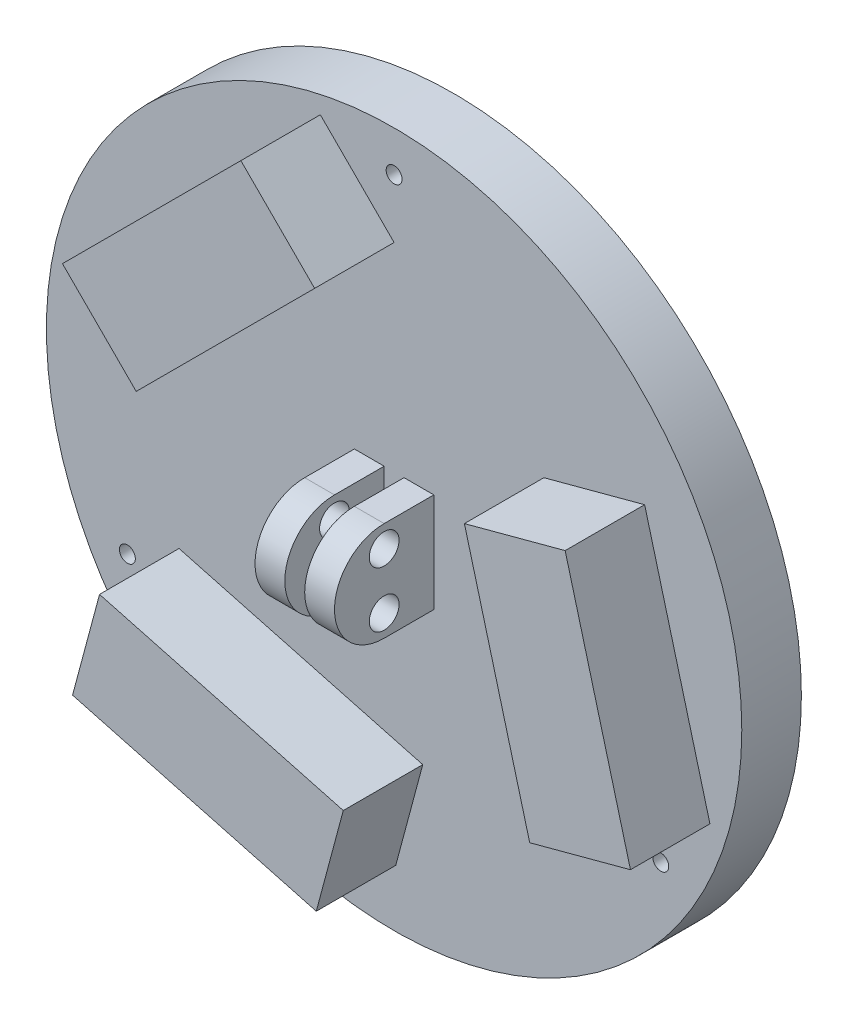
SolidWorks part; units mm, degrees
ref_plane "Front Plane" through (0, 0, 0) normal (0, 0, 1) x (1, 0, 0)
ref_plane "Top Plane" through (0, 0, 0) normal (0, 1, 0) x (1, 0, 0)
ref_plane "Right Plane" through (0, 0, 0) normal (1, 0, 0) x (0, 0, -1)
sketch "Sketch2" plane through (0, 0, 0) normal (0, 0, 1) x (1, 0, 0)
  circle A0 centre (0, 0) radius 35
  point P11 (0, 0)
  dimension "D1" = 70
extrude "Boss-Extrude1" add sketch "Sketch2" along normal blind 6 contours A0
sketch "Sketch3" plane through (0, 0, 6) normal (0, 0, 1) x (1, 0, 0)
  circle A0 centre (0, 30.9143) radius 0.8
  circle A1 centre (26.8468, -15.5857) radius 0.8
  circle A2 centre (-26.8468, -15.5857) radius 0.8
  point P8 (0, -0.0857)
  dimension "D1" = 1.6
  dimension "D3" = 31
  dimension "D2" = 3
extrude "Cut-Extrude1" cut sketch "Sketch3" against normal blind 6
sketch "Sketch4" plane through (0, 0, 6) normal (0, 0, 1) x (1, 0, 0)
  circle A0 centre (0, 0) radius 0.6
  dimension "D1" = 1.2
extrude "Cut-Extrude2" cut sketch "Sketch4" against normal blind 6
sketch "Sketch5" plane through (0, 0, 6) normal (0, 0, 1) x (1, 0, 0)
  line L1 (1, 5) -> (4, 5)
  line L2 (1, 5) -> (1, -5)
  line L3 (1, -5) -> (4, -5)
  line L4 (4, 5) -> (4, -5)
  line L5 (-1, 5) -> (-4, 5)
  line L6 (-1, 5) -> (-1, -5)
  line L7 (-1, -5) -> (-4, -5)
  line L8 (-4, 5) -> (-4, -5)
  dimension "D1" = 10
  dimension "D2" = 3
  dimension "D3" = 4
  dimension "D4" = 5
  dimension "D5" = 4
  dimension "D6" = 5
extrude "Boss-Extrude2" add sketch "Sketch5" along normal blind 10
sketch "Sketch6" plane through (4, 0, 0) normal (1, 0, 0) x (0, 0, -1)
  line L1 (-16, 5) -> (-6, 5) construction
  line L2 (-11, 5) -> (-16, 5)
  line L3 (-16, 5) -> (-16, -5)
  line L5 (-16, -5) -> (-11, -5)
  line L6 (-16, 5) -> (-11, 5)
  arc A2 (-11, -5) -> (-11, 5) centre (-11, 0) cw
  line M5 (-6, 5) -> (-16, 5)
  line M6 (-16, 5) -> (-16, -5)
  line M7 (-16, -5) -> (-6, -5)
extrude "Cut-Extrude3" cut sketch "Sketch6" against normal through all contours A2 M6 M5 | A2 L3 M7
sketch "Sketch7" plane through (4, 0, 0) normal (1, 0, 0) x (0, 0, -1)
  line L1 (-11, 5) -> (-6, 5) construction
  line L2 (-11, -5) -> (-6, -5) construction
  circle A2 centre (-11, 2.8) radius 1.5
  circle A3 centre (-11, -2.8) radius 1.5
  dimension "D1" = 2.2
  dimension "D2" = 2.2
  dimension "D4" = 3
extrude "Cut-Extrude4" cut sketch "Sketch7" against normal through all
sketch "Sketch8" plane through (0, 0, 6) normal (0, 0, 1) x (1, 0, 0)
  line L0 (-7.4246, 32.4246) -> (0, 25)
  line L1 (-7.4246, 32.4246) -> (-25.3851, 14.4641)
  line L2 (0, 25) -> (-17.9605, 7.0395)
  line L3 (-25.3851, 14.4641) -> (-17.9605, 7.0395)
  line L4 (31.7929, -9.7824) -> (21.6506, -12.5)
  line L5 (31.7929, -9.7824) -> (25.2189, 14.7521)
  line L6 (25.2189, 14.7521) -> (15.0766, 12.0345)
  line L7 (21.6506, -12.5) -> (15.0766, 12.0345)
  line L8 (-24.3682, -22.6422) -> (-21.6506, -12.5)
  line L9 (-24.3682, -22.6422) -> (0.1663, -29.2162)
  line L10 (0.1663, -29.2162) -> (2.8839, -19.074)
  line L11 (-21.6506, -12.5) -> (2.8839, -19.074)
  line L12 (0, 0) -> (0, 40.2175) construction
  point P3 (0, 0)
  point P16 (0, 0)
  point P17 (0, 0)
  dimension "D1" = 25.4
  dimension "D2" = 10.5
  dimension "D3" = 25
  dimension "D5" = 45
  dimension "D4" = 3
extrude "Boss-Extrude3" add sketch "Sketch8" along normal blind 8
